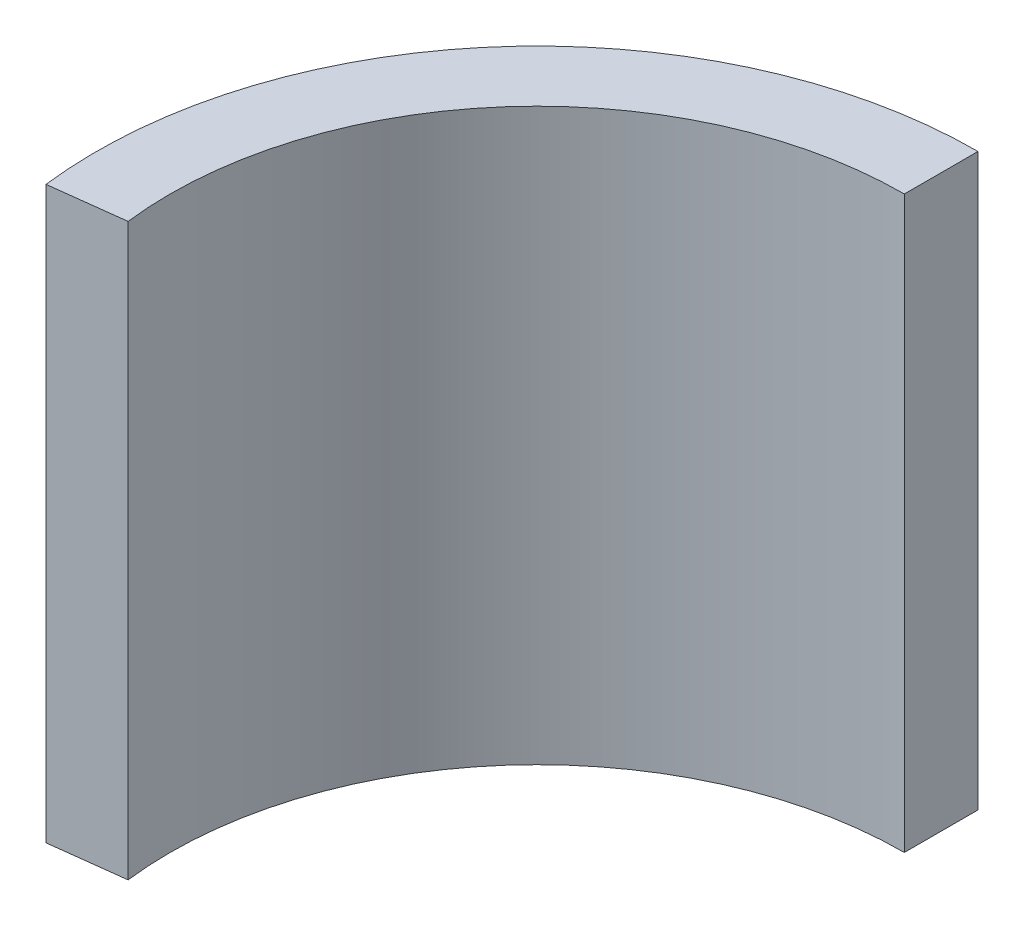
SolidWorks part; units mm, degrees
ref_plane "Front Plane" through (0, 0, 0) normal (0, 0, 1) x (1, 0, 0)
ref_plane "Top Plane" through (0, 0, 0) normal (0, 1, 0) x (1, 0, 0)
ref_plane "Right Plane" through (0, 0, 0) normal (1, 0, 0) x (0, 0, -1)
sketch "RevolveSketch" plane through (0, 0, 0) normal (1, 0, 0) x (0, 0, -1)
  line L0 (11, -9) -> (11, 15)
  line L1 (-6, -18) -> (-6, 26) construction
revolve "ThinBossRevolve" add sketch "RevolveSketch" angle 97 about L1
